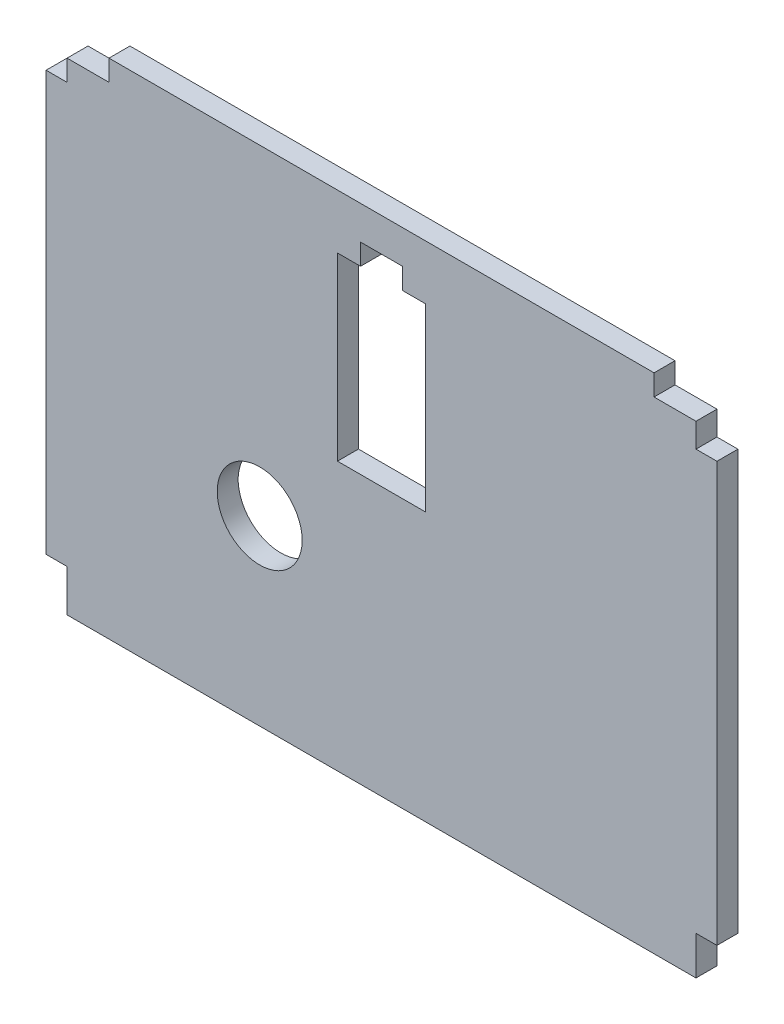
SolidWorks part; units mm, degrees
ref_plane "Plan de face" through (0, 0, 0) normal (0, 0, 1) x (1, 0, 0)
ref_plane "Plan de dessus" through (0, 0, 0) normal (0, 1, 0) x (1, 0, 0)
ref_plane "Plan de droite" through (0, 0, 0) normal (1, 0, 0) x (0, 0, -1)
sketch "Esquisse1" plane through (0, 0, 0) normal (0, 0, 1) x (1, 0, 0)
  line L0 (-81.0433, -69.9713) -> (68.9567, -69.9713)
  line L14 (68.9567, -69.9713) -> (68.9567, -60.7378)
  line L15 (68.9567, -60.7378) -> (73.9567, -60.7378)
  line L17 (-86.0433, -59.9713) -> (-81.0433, -59.9713)
  line L20 (-81.0433, -59.9713) -> (-81.0433, -69.9713)
  line L21 (73.9567, -60.7378) -> (73.9567, 39.2622)
  line L22 (58.9567, 50.0287) -> (-71.0433, 50.0287)
  line L23 (-86.0433, 40.0287) -> (-86.0433, -59.9713)
  line L24 (68.9567, 39.2622) -> (73.9567, 39.2622)
  line L27 (-71.0433, 45.0287) -> (-81.0433, 45.0287)
  line L28 (-81.0433, 40.0287) -> (-81.0433, 45.0287)
  line L31 (58.9567, 45.0287) -> (68.9567, 45.0287)
  line L32 (68.9567, 39.2622) -> (68.9567, 45.0287)
  line L33 (58.9567, 45.0287) -> (58.9567, 50.0287)
  line L34 (-71.0433, 45.0287) -> (-71.0433, 50.0287)
  line L35 (-86.0433, 40.0287) -> (-81.0433, 40.0287)
  dimension "D2" = 120
  dimension "D3" = 160
  dimension "D4" = 100
  dimension "D5" = 150
  dimension "D6" = 5
  dimension "D7" = 5
  dimension "D8" = 5
  dimension "D12" = 5
extrude "Boss.-Extru.2" add sketch "Esquisse1" along normal blind 5 contours L22 L34 L27 L28 L35 L23 L17 L20 L0 L14 L15 L21 L24 L32 L31 L33
sketch "Esquisse3" plane through (0, 0, 5) normal (0, 0, 1) x (1, 0, 0)
  line L2 (-16.5433, 37.0287) -> (-16.5433, -5.9713)
  line L3 (-16.5433, -5.9713) -> (4.4567, -5.9713)
  line L4 (4.4567, 37.0287) -> (4.4567, -5.9713)
  line L5 (73.9567, -60.7378) -> (73.9567, 39.2622) construction
  line L6 (-16.5433, 37.0287) -> (-11.0433, 37.0287)
  line L9 (-6.0433, 42.0287) -> (-1.0433, 42.0287)
  line L10 (-1.0433, 37.0287) -> (-1.0433, 42.0287)
  line L11 (-6.0433, 42.0287) -> (-11.0433, 42.0287)
  line L14 (-11.0433, 42.0287) -> (-11.0433, 37.0287)
  line L15 (-1.0433, 37.0287) -> (4.4567, 37.0287)
  point P8 (-6.0433, -5.9713)
  dimension "D1" = 21
  dimension "D5" = 80
  dimension "D8" = 5
extrude "Enlèv. mat.-Extru.1" cut sketch "Esquisse3" against normal blind 5
sketch "Esquisse4" plane through (0, 0, 5) normal (0, 0, 1) x (1, 0, 0)
  circle A0 centre (-35.0986, -26.5621) radius 10.1334
  point P2 (-35.0986, -26.5621)
extrude "Enlèv. mat.-Extru.2" cut sketch "Esquisse4" against normal blind 10
